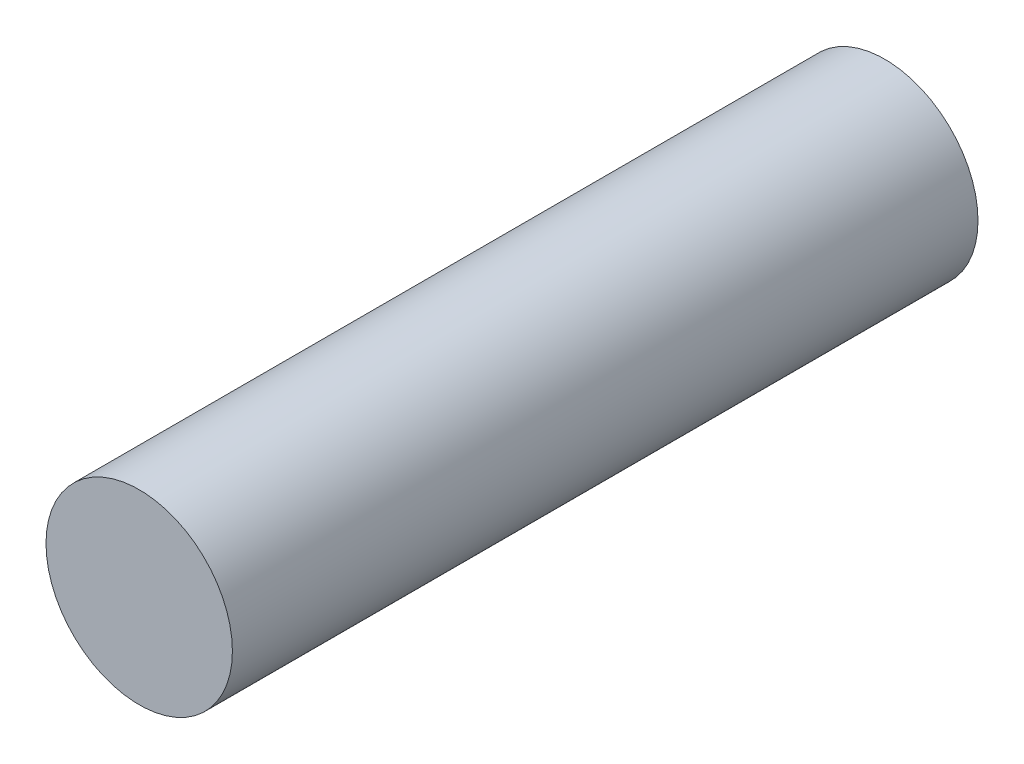
SolidWorks part; units mm, degrees
ref_plane "Front Plane" through (0, 0, 0) normal (0, 0, 1) x (1, 0, 0)
ref_plane "Top Plane" through (0, 0, 0) normal (0, 1, 0) x (1, 0, 0)
ref_plane "Right Plane" through (0, 0, 0) normal (1, 0, 0) x (0, 0, -1)
sketch "Sketch1" plane through (0, 0, 0) normal (0, 0, 1) x (1, 0, 0)
  circle A0 centre (0, 0) radius 12.7
extrude "Boss-Extrude1" add sketch "Sketch1" along normal blind 101.6
